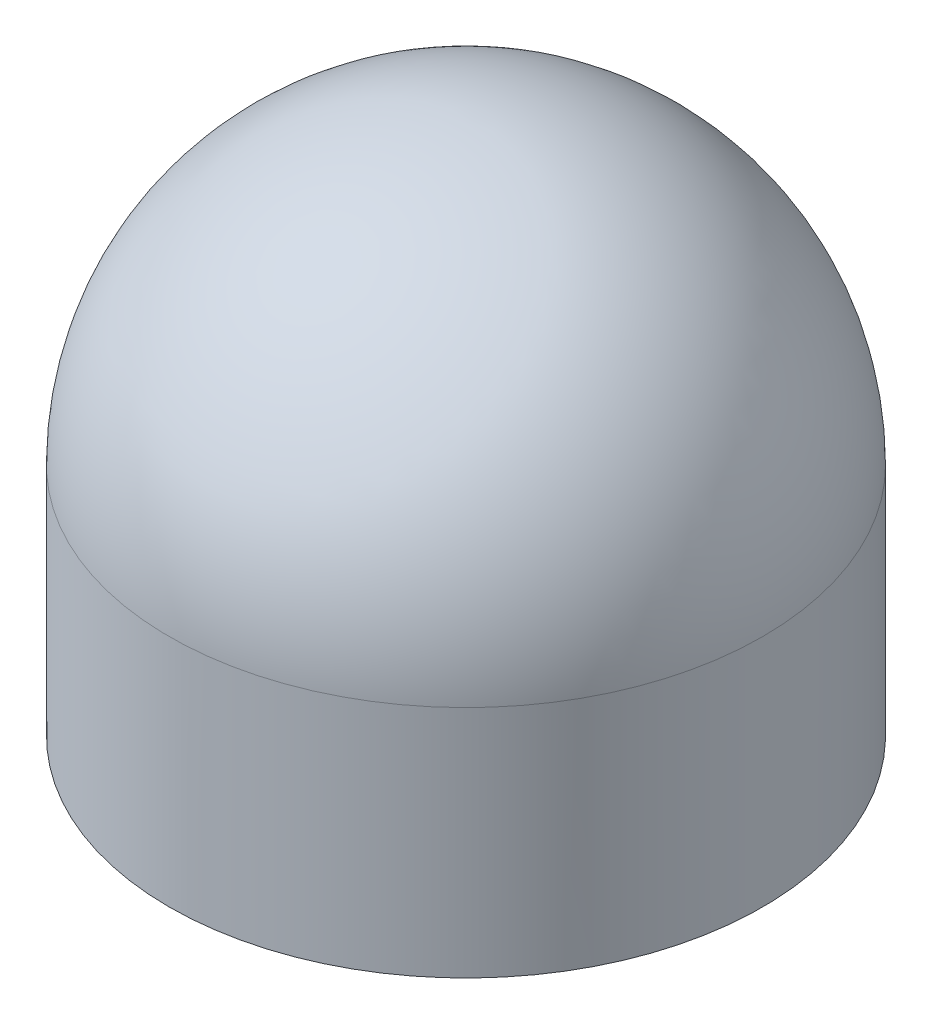
SolidWorks part; units mm, degrees
ref_plane "Front Plane" through (0, 0, 0) normal (0, 0, 1) x (1, 0, 0)
ref_plane "Top Plane" through (0, 0, 0) normal (0, 1, 0) x (1, 0, 0)
ref_plane "Right Plane" through (0, 0, 0) normal (1, 0, 0) x (0, 0, -1)
sketch "Sketch2" plane through (0, 0, 0) normal (0, 0, 1) x (1, 0, 0)
  line L0 (0, 7.62) -> (0, 17.272)
  line L1 (0, 0) -> (9.652, 0)
  line L2 (0, 0) -> (0, 7.62)
  line L4 (9.652, 0) -> (9.652, 7.62)
  arc A0 (9.652, 7.62) -> (0, 17.272) centre (0, 7.62) ccw
  dimension "D1" = 7.62
  dimension "D2" = 9.652
revolve "Revolve1" add sketch "Sketch2" angle 360 about L0
